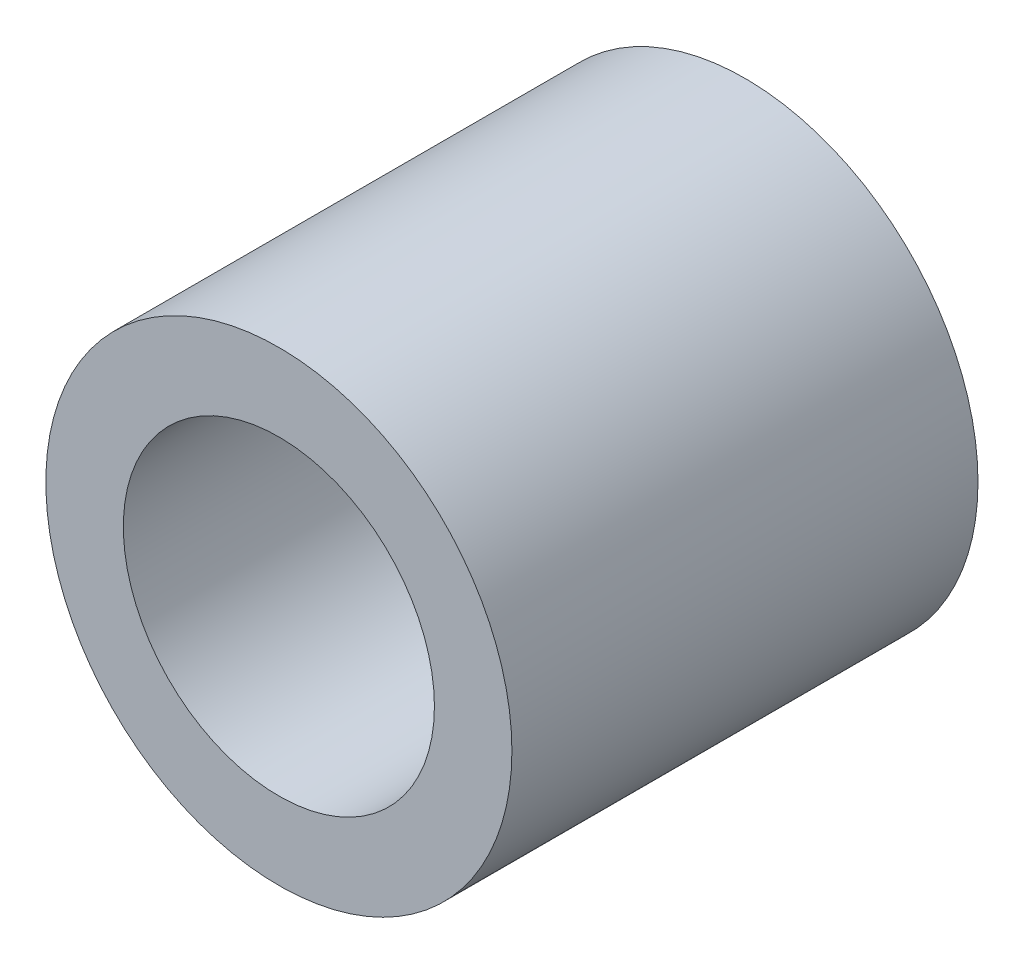
SolidWorks part; units mm, degrees
ref_plane "Front Plane" through (0, 0, 0) normal (0, 0, 1) x (1, 0, 0)
ref_plane "Top Plane" through (0, 0, 0) normal (0, 1, 0) x (1, 0, 0)
ref_plane "Right Plane" through (0, 0, 0) normal (1, 0, 0) x (0, 0, -1)
sketch "Sketch1" plane through (0, 0, 0) normal (0, 0, 1) x (1, 0, 0)
  circle A0 centre (0, 0) radius 4.7625
  circle A1 centre (0, 0) radius 3.1788
  point P4 (0, 4.7625)
  dimension "OD" = 9.525
  dimension "ID" = 6.3576
sketch "Sketch2" plane through (0, 0, 0) normal (1, 0, 0) x (0, 0, -1)
  line L0 (4.7625, 0) -> (-4.7625, 0) construction
  line L1 (4.7625, 4.7625) -> (-4.7625, 4.7625) construction
  point P4 (0, 0)
  point P9 (0, 4.7625)
  dimension "Length" = 9.525
sketch "Sketch3" plane through (0, 0, 0) normal (0, 0, 1) x (1, 0, 0)
  circle A0 centre (0, 0) radius 4.7625 construction
  circle A1 centre (0, 0) radius 3.1788 construction
  circle A2 centre (0, 0) radius 4.7625
  circle A3 centre (0, 0) radius 3.1788
extrude "Boss-Extrude1" add sketch "Sketch3" against normal up to vertex (4.7625 mm away) and the other way up to vertex (4.7625 mm away) up to point (0, 0, -4.7625) other way up to point (0, 0, 4.7625)
